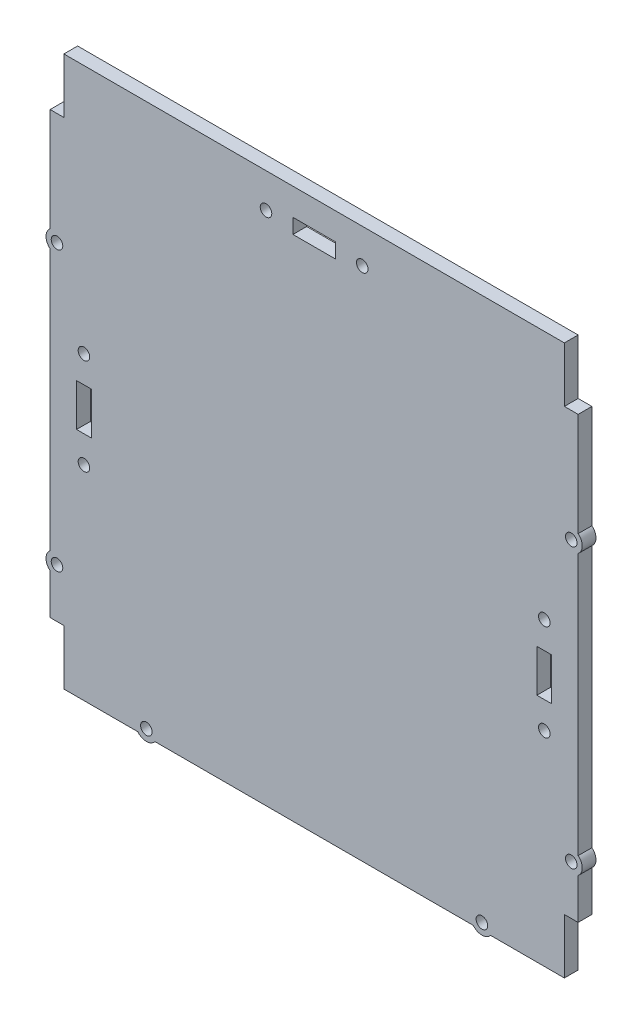
SolidWorks part; units mm, degrees
ref_plane "Front Plane" through (0, 0, 0) normal (0, 0, 1) x (1, 0, 0)
ref_plane "Top Plane" through (0, 0, 0) normal (0, 1, 0) x (1, 0, 0)
ref_plane "Right Plane" through (0, 0, 0) normal (1, 0, 0) x (0, 0, -1)
sketch "Sketch1" plane through (0, 0, 0) normal (0, 0, 1) x (1, 0, 0)
  line L0 (-182, 200) -> (-182, 180)
  line L1 (-182, 180) -> (-187, 180)
  line L2 (-187, 180) -> (-187, 20)
  line L3 (-187, 20) -> (-182, 20)
  line L4 (-182, 20) -> (-182, 0)
  line L5 (-182, 0) -> (0, 0)
  line L6 (0, 0) -> (0, 20)
  line L7 (0, 20) -> (5, 20)
  line L8 (5, 20) -> (5, 180)
  line L9 (5, 180) -> (0, 180)
  line L10 (0, 180) -> (0, 200)
  line L11 (0, 200) -> (-182, 200)
  dimension "D1" = 182
  dimension "D2" = 160
  dimension "D3" = 20
  dimension "D4" = 20
  dimension "D5" = 5
  dimension "D6" = 5
  dimension "D7" = 5
  dimension "D8" = 5
  dimension "D9" = 20
  dimension "D10" = 20
extrude "Boss-Extrude1" add sketch "Sketch1" along normal blind 5
sketch "Sketch2" plane through (0, 0, 0) normal (0, 0, -1) x (-1, 0, 0)
  line L0 (0, 200) -> (182, 200) construction
  line L1 (-5, 20) -> (-5, 180) construction
  line L3 (182, 0) -> (0, 0) construction
  line L4 (91, 200) -> (91, 0) construction
  circle A0 centre (-2.5, 139.3) radius 2.1
  circle A1 centre (-2.5, 37.9) radius 2.1
  circle A2 centre (184.5, 37.9) radius 2.1
  circle A3 centre (184.5, 139.3) radius 2.1
  dimension "D1" = 4.2
  dimension "D3" = 2.5
  dimension "D4" = 4.2
  dimension "D5" = 2.5
  dimension "D6" = 37.9
  dimension "D2" = 60.7
extrude "Cut-Extrude1" cut sketch "Sketch2" against normal blind 10
sketch "Sketch3" plane through (0, 0, 0) normal (0, 0, -1) x (-1, 0, 0)
  line L0 (-5, 20) -> (-5, 180) construction
  line L1 (-5, 136.1775) -> (-5, 142.4225)
  arc A0 (-5, 142.4225) -> (-5, 136.1775) centre (-2.5, 139.3) ccw
  dimension "D1" = 8
extrude "Boss-Extrude2" add sketch "Sketch3" against normal blind 5
sketch "Sketch4" plane through (0, 0, 0) normal (0, 0, -1) x (-1, 0, 0)
  line L0 (-5, 20) -> (-5, 136.1775) construction
  line L1 (-5, 34.7775) -> (-5, 41.0225)
  arc A0 (-5, 41.0225) -> (-5, 34.7775) centre (-2.5, 37.9) ccw
extrude "Boss-Extrude3" add sketch "Sketch4" against normal blind 5
ref_plane "Plane1" through (-91, 0, 0) normal (-1, 0, 0) x (0, 0, 1)
mirror "Mirror1" about plane through (-91, 0, 0) normal (-1, 0, 0) of "Boss-Extrude2", "Boss-Extrude3"
sketch "Sketch5" plane through (0, 0, 0) normal (0, 0, -1) x (-1, 0, 0)
  line L0 (182, 0) -> (0, 0) construction
  line L1 (182, 20) -> (182, 0) construction
  line L2 (0, 0) -> (0, 20) construction
  circle A0 centre (30, 2.5) radius 2.1
  circle A1 centre (152, 2.5) radius 2.1
  dimension "D1" = 2.5
  dimension "D3" = 30
  dimension "D2" = 2.5
  dimension "D4" = 30
extrude "Cut-Extrude2" cut sketch "Sketch5" against normal blind 5
sketch "Sketch6" plane through (0, 0, 0) normal (0, 0, -1) x (-1, 0, 0)
  line L0 (182, 0) -> (0, 0) construction
  line L1 (155.1225, 0) -> (148.8775, 0)
  line L2 (33.1225, 0) -> (26.8775, 0)
  arc A0 (26.8775, 0) -> (33.1225, 0) centre (30, 2.5) ccw
  arc A1 (148.8775, 0) -> (155.1225, 0) centre (152, 2.5) ccw
extrude "Boss-Extrude4" add sketch "Sketch6" against normal blind 5
sketch "Sketch8" plane through (0, 0, 0) normal (0, 0, -1) x (-1, 0, 0)
  line L0 (81, 15) -> (66, 15) construction
  line L1 (66, 15) -> (66, 10) construction
  line L2 (66, 10) -> (81, 10) construction
  line L3 (81, 10) -> (81, 15) construction
  line L4 (116, 15) -> (101, 15) construction
  line L5 (101, 15) -> (101, 10) construction
  line L6 (101, 10) -> (116, 10) construction
  line L7 (116, 10) -> (116, 15) construction
  line L8 (81, 15) -> (66, 15)
  line L9 (66, 15) -> (66, 10)
  line L10 (66, 10) -> (81, 10)
  line L11 (81, 10) -> (81, 15)
  line L12 (116, 15) -> (101, 15)
  line L13 (101, 15) -> (101, 10)
  line L14 (101, 10) -> (116, 10)
  line L15 (116, 10) -> (116, 15)
  line L16 (172, 90) -> (172.0286, 110) construction
  line L17 (177, 90) -> (172, 90) construction
  line L18 (172, 75) -> (172, 90) construction
  line L19 (177, 110) -> (172, 110) construction
  line L20 (172.0143, 100) -> (55.2635, 100) construction
  line L21 (116.2, 190.2) -> (116.2, 184.8)
  line L22 (100.8, 190.2) -> (116.2, 190.2)
  line L23 (100.8, 184.8) -> (100.8, 190.2)
  line L24 (81.2, 15.2) -> (65.8, 15.2)
  line L25 (65.8, 15.2) -> (65.8, 9.8)
  line L26 (65.8, 9.8) -> (81.2, 9.8)
  line L27 (81.2, 9.8) -> (81.2, 15.2)
  line L28 (81.2, 15.2) -> (65.8, 15.2)
  line L29 (65.8, 15.2) -> (65.8, 9.8)
  line L30 (65.8, 9.8) -> (81.2, 9.8)
  line L31 (81.2, 9.8) -> (81.2, 15.2)
  line L32 (100.8, 12.5) -> (81.2, 12.5) construction
  line L33 (116.2, 184.8) -> (100.8, 184.8)
  line L34 (81.2, 190.2) -> (81.2, 184.8)
  line L35 (65.8, 190.2) -> (81.2, 190.2)
  line L36 (116.2, 15.2) -> (100.8, 15.2)
  line L37 (100.8, 15.2) -> (100.8, 9.8)
  line L38 (100.8, 9.8) -> (116.2, 9.8)
  line L39 (116.2, 9.8) -> (116.2, 15.2)
  line L40 (116.2, 15.2) -> (100.8, 15.2)
  line L41 (100.8, 15.2) -> (100.8, 9.8)
  line L42 (100.8, 9.8) -> (116.2, 9.8)
  line L43 (116.2, 9.8) -> (116.2, 15.2)
  line L44 (65.8, 184.8) -> (65.8, 190.2)
  line L45 (81.2, 184.8) -> (65.8, 184.8)
  line L46 (116, 190) -> (116, 185)
  line L47 (101, 190) -> (116, 190)
  line L48 (101, 185) -> (101, 190)
  line L49 (116, 185) -> (101, 185)
  line L50 (81, 190) -> (81, 185)
  line L51 (66, 190) -> (81, 190)
  line L52 (66, 185) -> (66, 190)
  line L53 (81, 185) -> (66, 185)
  line L54 (172, 125) -> (172, 110) construction
  line L55 (172, 110) -> (177, 110) construction
  line L56 (177, 110) -> (177, 125) construction
  line L57 (177, 125) -> (172, 125) construction
  line L58 (172, 90) -> (172, 75) construction
  line L59 (172, 75) -> (177, 75) construction
  line L60 (177, 75) -> (177, 90) construction
  line L61 (172, 125) -> (172, 110)
  line L62 (172, 110) -> (177, 110)
  line L63 (177, 110) -> (177, 125)
  line L64 (177, 125) -> (172, 125)
  line L65 (172, 90) -> (172, 75)
  line L66 (172, 75) -> (177, 75)
  line L67 (177, 75) -> (177, 90)
  line L68 (177, 90) -> (172, 90)
  line L69 (5, 125) -> (5, 110) construction
  line L70 (5, 110) -> (10, 110) construction
  line L71 (10, 110) -> (10, 125) construction
  line L72 (10, 125) -> (5, 125) construction
  line L73 (5, 90) -> (5, 75) construction
  line L74 (5, 75) -> (10, 75) construction
  line L75 (10, 75) -> (10, 90) construction
  line L76 (10, 90) -> (5, 90) construction
  line L77 (5, 125) -> (5, 110)
  line L78 (5, 110) -> (10, 110)
  line L79 (10, 110) -> (10, 125)
  line L80 (10, 125) -> (5, 125)
  line L81 (5, 90) -> (5, 75)
  line L82 (5, 75) -> (10, 75)
  line L83 (10, 75) -> (10, 90)
  line L84 (10, 90) -> (5, 90)
  line L93 (171.8, 90.2) -> (171.8, 74.8)
  line L94 (171.8, 74.8) -> (177.2, 74.8)
  line L95 (177.2, 74.8) -> (177.2, 90.2)
  line L96 (177.2, 90.2) -> (171.8, 90.2)
  line L97 (171.8, 90.2) -> (171.8, 74.8)
  line L98 (171.8, 74.8) -> (177.2, 74.8)
  line L99 (177.2, 74.8) -> (177.2, 90.2)
  line L100 (177.2, 90.2) -> (171.8, 90.2)
  line L105 (171.8, 125.2) -> (171.8, 109.8)
  line L106 (171.8, 109.8) -> (177.2, 109.8)
  line L107 (177.2, 109.8) -> (177.2, 125.2)
  line L108 (177.2, 125.2) -> (171.8, 125.2)
  line L109 (171.8, 125.2) -> (171.8, 109.8)
  line L110 (171.8, 109.8) -> (177.2, 109.8)
  line L111 (177.2, 109.8) -> (177.2, 125.2)
  line L112 (177.2, 125.2) -> (171.8, 125.2)
  line L117 (4.8, 90.2) -> (4.8, 74.8)
  line L118 (4.8, 74.8) -> (10.2, 74.8)
  line L119 (10.2, 74.8) -> (10.2, 90.2)
  line L120 (10.2, 90.2) -> (4.8, 90.2)
  line L121 (4.8, 90.2) -> (4.8, 74.8)
  line L122 (4.8, 74.8) -> (10.2, 74.8)
  line L123 (10.2, 74.8) -> (10.2, 90.2)
  line L124 (10.2, 90.2) -> (4.8, 90.2)
  line L125 (172.0143, 100) -> (176.9857, 100)
  line L126 (91, 12.5) -> (91, 40.5503) construction
  line L129 (4.8, 125.2) -> (4.8, 109.8)
  line L130 (4.8, 109.8) -> (10.2, 109.8)
  line L131 (10.2, 109.8) -> (10.2, 125.2)
  line L132 (10.2, 125.2) -> (4.8, 125.2)
  line L133 (4.8, 125.2) -> (4.8, 109.8)
  line L134 (4.8, 109.8) -> (10.2, 109.8)
  line L135 (10.2, 109.8) -> (10.2, 125.2)
  line L136 (10.2, 125.2) -> (4.8, 125.2)
  circle A0 centre (91, 12.5) radius 2.1
  circle A1 centre (91, 187.5) radius 2.1
  circle A2 centre (174.5, 100) radius 2.1
  circle A3 centre (7.5, 100) radius 2.1
  dimension "D3" = 4.2
  dimension "D8" = 4.2
  dimension "D9" = 2.5
  dimension "D1" = 0.2
  dimension "D2" = 0.2
  dimension "D4" = 0.2
  dimension "D5" = 0.2
  dimension "D6" = 0.2
  dimension "D7" = 0.2
extrude "Cut-Extrude5" [suppressed] cut sketch "Sketch8" against normal blind 5 contours L10 L11 L8 L9 | L30 L31 L28 L29 | A0 | L40 L41 L42 L43 | L100 L97 L98 L99 | A2 | L110 L111 L112 L109 | L22 L21 L33 L23 | A1 | L34 L45 L44 L35 | L134 L135 L136 L133 | A3 | L124 L121 L122 L123
sketch "Sketch9" plane through (0, 0, 5) normal (0, 0, 1) x (1, 0, 0)
  line L4 (0, 200) -> (-182, 200)
  line L5 (0, 200) -> (-182, 200)
  line L6 (-182, 200) -> (-182, 180)
  line L7 (-182, 200) -> (-182, 180)
  line L26 (-182, 180) -> (-187, 180)
  line L27 (-182, 180) -> (-187, 180)
  line L28 (-187, 180) -> (-187, 142.4225)
  line L29 (-187, 180) -> (-187, 142.4225)
  line L30 (-187, 136.1775) -> (-187, 41.0225)
  line L31 (-187, 136.1775) -> (-187, 41.0225)
  line L32 (-187, 34.7775) -> (-187, 20)
  line L33 (-187, 34.7775) -> (-187, 20)
  line L34 (-187, 20) -> (-182, 20)
  line L35 (-187, 20) -> (-182, 20)
  line L36 (-182, 20) -> (-182, 0)
  line L37 (-182, 20) -> (-182, 0)
  line L38 (-182, 0) -> (-155.1225, 0)
  line L39 (-182, 0) -> (-155.1225, 0)
  line L40 (-148.8775, 0) -> (-33.1225, 0)
  line L41 (-148.8775, 0) -> (-33.1225, 0)
  line L42 (-26.8775, 0) -> (0, 0)
  line L43 (-26.8775, 0) -> (0, 0)
  line L44 (0, 0) -> (0, 20)
  line L45 (0, 0) -> (0, 20)
  line L46 (0, 20) -> (5, 20)
  line L47 (0, 20) -> (5, 20)
  line L48 (5, 20) -> (5, 34.7775)
  line L49 (5, 20) -> (5, 34.7775)
  line L50 (5, 41.0225) -> (5, 136.1775)
  line L51 (5, 41.0225) -> (5, 136.1775)
  line L52 (5, 142.4225) -> (5, 180)
  line L53 (5, 142.4225) -> (5, 180)
  line L54 (5, 180) -> (0, 180)
  line L55 (5, 180) -> (0, 180)
  line L56 (0, 180) -> (0, 200)
  line L57 (0, 180) -> (0, 200)
  arc A6 (-187, 142.4225) -> (-187, 136.1775) centre (-184.5, 139.3) ccw
  arc A7 (-187, 142.4225) -> (-187, 136.1775) centre (-184.5, 139.3) ccw
  arc A8 (-187, 41.0225) -> (-187, 34.7775) centre (-184.5, 37.9) ccw
  arc A9 (-187, 41.0225) -> (-187, 34.7775) centre (-184.5, 37.9) ccw
  arc A10 (-155.1225, 0) -> (-148.8775, 0) centre (-152, 2.5) ccw
  arc A11 (-155.1225, 0) -> (-148.8775, 0) centre (-152, 2.5) ccw
  arc A12 (-33.1225, 0) -> (-26.8775, 0) centre (-30, 2.5) ccw
  arc A13 (-33.1225, 0) -> (-26.8775, 0) centre (-30, 2.5) ccw
  arc A14 (5, 34.7775) -> (5, 41.0225) centre (2.5, 37.9) ccw
  arc A15 (5, 34.7775) -> (5, 41.0225) centre (2.5, 37.9) ccw
  arc A16 (5, 136.1775) -> (5, 142.4225) centre (2.5, 139.3) ccw
  arc A17 (5, 136.1775) -> (5, 142.4225) centre (2.5, 139.3) ccw
  dimension "D1" = 0
extrude "Cut-Extrude6" [suppressed] cut sketch "Sketch9" against normal blind 10
sketch "Sketch10" plane through (0, 0, 0) normal (0, 0, -1) x (-1, 0, 0)
  line L0 (91, 185) -> (91, -1.5057) construction
  line L1 (10, 84.0471) -> (4.6, 84.0471)
  line L2 (10, 84.0471) -> (10, 99.4471)
  line L3 (10, 99.4471) -> (4.6, 99.4471)
  line L4 (98.5, -1.5057) -> (83.5, -1.5057)
  line L5 (83.5, -1.5057) -> (83.5, -6.5057)
  line L6 (83.5, -6.5057) -> (98.5, -6.5057)
  line L7 (98.5, -6.5057) -> (98.5, -1.5057)
  line L8 (98.5, -1.5057) -> (83.5, -1.5057)
  line L9 (83.5, -1.5057) -> (83.5, -6.5057)
  line L10 (83.5, -6.5057) -> (98.5, -6.5057)
  line L11 (98.5, -6.5057) -> (98.5, -1.5057)
  line L12 (4.6, 84.0471) -> (4.6, 99.4471)
  line L13 (177.4, 84.0471) -> (177.4, 99.4471)
  line L14 (172, 99.4471) -> (177.4, 99.4471)
  line L15 (172, 84.0471) -> (172, 99.4471)
  line L16 (98.5, 190) -> (83.5, 190)
  line L17 (83.5, 190) -> (83.5, 185)
  line L18 (83.5, 185) -> (98.5, 185)
  line L19 (98.5, 185) -> (98.5, 190)
  line L20 (98.5, 190) -> (83.5, 190)
  line L21 (83.5, 190) -> (83.5, 185)
  line L22 (83.5, 185) -> (98.5, 185)
  line L23 (98.5, 185) -> (98.5, 190)
  line L24 (172, 84.0471) -> (177.4, 84.0471)
  line L25 (98.7, -1.3057) -> (83.3, -1.3057)
  line L26 (83.3, -1.3057) -> (83.3, -6.7057)
  line L27 (83.3, -6.7057) -> (98.7, -6.7057)
  line L28 (98.7, -6.7057) -> (98.7, -1.3057)
  line L29 (98.7, 190.2) -> (83.3, 190.2)
  line L30 (83.3, 190.2) -> (83.3, 184.8)
  line L31 (83.3, 184.8) -> (98.7, 184.8)
  line L32 (98.7, 184.8) -> (98.7, 190.2)
  point P14 (10, 91.7471)
  point P15 (91, 91.7471)
  dimension "D2" = 15.4
  dimension "D3" = 5.4
  dimension "D5" = 81
  dimension "D1" = 0
  dimension "D4" = 0
  dimension "D6" = 0.2
  dimension "D7" = 0.2
extrude "Cut-Extrude7" cut sketch "Sketch10" against normal blind 10
sketch "Sketch11" plane through (0, 0, 5) normal (0, 0, 1) x (1, 0, 0)
  line L0 (-83.5, 15) -> (-98.5, 15) construction
  line L1 (-98.5, 15) -> (-98.5, 10) construction
  line L2 (-98.5, 10) -> (-83.5, 10) construction
  line L3 (-83.5, 10) -> (-83.5, 15) construction
  line L4 (-83.5, 190) -> (-98.5, 190) construction
  line L5 (-98.5, 190) -> (-98.5, 185) construction
  line L6 (-98.5, 185) -> (-83.5, 185) construction
  line L7 (-83.5, 185) -> (-83.5, 190) construction
  line L8 (-83.5, 15) -> (-98.5, 15)
  line L9 (-98.5, 15) -> (-98.5, 10)
  line L10 (-98.5, 10) -> (-83.5, 10)
  line L11 (-83.5, 10) -> (-83.5, 15)
  line L12 (-83.5, 190) -> (-98.5, 190)
  line L13 (-98.5, 190) -> (-98.5, 185)
  line L14 (-98.5, 185) -> (-83.5, 185)
  line L15 (-83.5, 185) -> (-83.5, 190)
extrude "Cut-Extrude8" cut sketch "Sketch11" against normal blind 10
sketch "Sketch12" plane through (0, 0, 5) normal (0, 0, 1) x (1, 0, 0)
  line L1 (-83.3, 190.2) -> (-98.7, 190.2) construction
  line L2 (-91, 190.2) -> (-91, 171.7455) construction
  line L3 (-91, 2.75) -> (-91, -2.75) construction
  line L4 (-172, 91.7471) -> (-155.2731, 91.7471) construction
  line L5 (-172, 84.0471) -> (-172, 99.4471) construction
  line L6 (-91, -6.7057) -> (-91, 11.7488) construction
  line L7 (-172, 99.4471) -> (-177.4, 99.4471) construction
  line L8 (-10, 91.7471) -> (-26.7269, 91.7471) construction
  circle A0 centre (-108.5, 187.5) radius 2.1
  circle A1 centre (-73.5, 187.5) radius 2.1
  circle A2 centre (-73.5, -4.0057) radius 2.1
  circle A3 centre (-108.5, -4.0057) radius 2.1
  circle A4 centre (-174.7, 109.2471) radius 2.1
  circle A5 centre (-174.7, 74.2471) radius 2.1
  circle A6 centre (-7.3, 74.2471) radius 2.1
  circle A7 centre (-7.3, 109.2471) radius 2.1
  point P6 (-91, 190.2)
  point P25 (-174.7, 99.4471)
  point P28 (-174.7, 84.0471)
  point P35 (-7.3, 84.0471)
  dimension "D1" = 4.2
  dimension "D2" = 17.5
  dimension "D4" = 4.2
  dimension "D5" = 17.5
  dimension "D3" = 2.7
extrude "Cut-Extrude9" cut sketch "Sketch12" against normal blind 10
